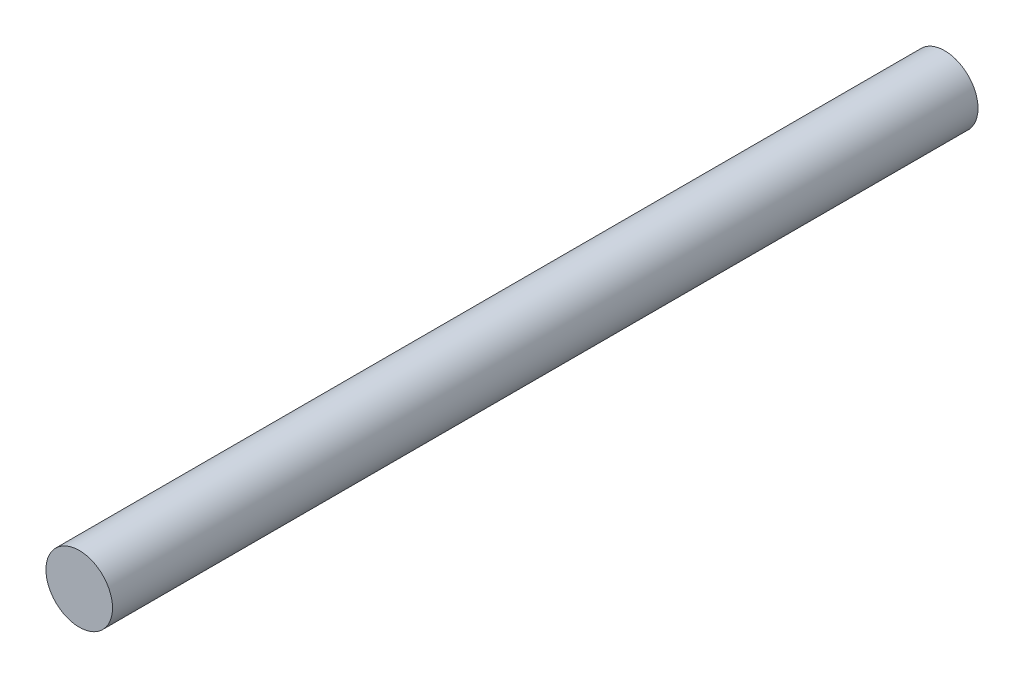
SolidWorks part; units mm, degrees
ref_plane "Front Plane" through (0, 0, 0) normal (0, 0, 1) x (1, 0, 0)
ref_plane "Top Plane" through (0, 0, 0) normal (0, 1, 0) x (1, 0, 0)
ref_plane "Right Plane" through (0, 0, 0) normal (1, 0, 0) x (0, 0, -1)
sketch "Sketch1" plane through (0, 0, 0) normal (0, 0, 1) x (1, 0, 0)
  circle A0 centre (-5.1467, 5.6335) radius 3.175
  dimension "D1" = 6.35
extrude "Boss-Extrude1" add sketch "Sketch1" along normal blind 82.55
